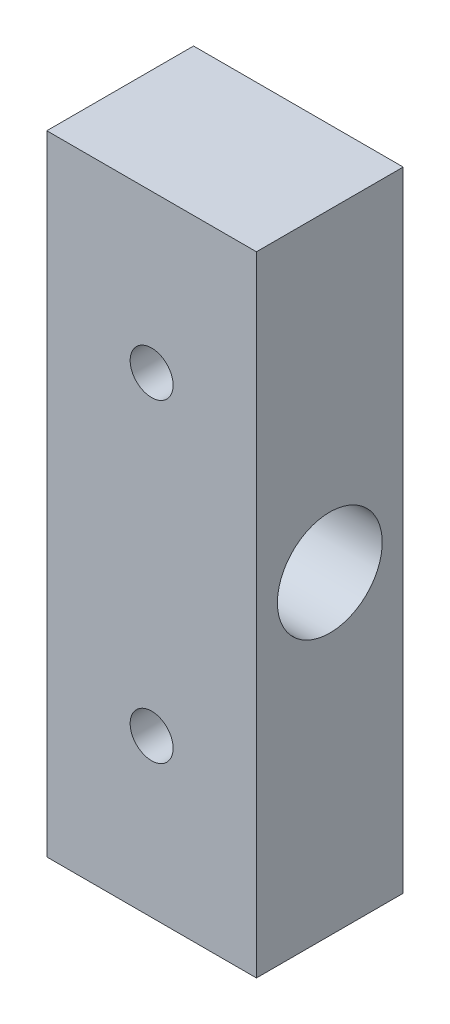
SolidWorks part; units mm, degrees
ref_plane "前视基准面" through (0, 0, 0) normal (0, 0, 1) x (1, 0, 0)
ref_plane "上视基准面" through (0, 0, 0) normal (0, 1, 0) x (1, 0, 0)
ref_plane "右视基准面" through (0, 0, 0) normal (1, 0, 0) x (0, 0, -1)
other "Configuration Table"
sketch "草图1" plane through (0, 0, 0) normal (0, 1, 0) x (1, 0, 0)
  line L1 (-10, 7) -> (10, 7)
  line L2 (-10, 7) -> (-10, -7)
  line L3 (-10, -7) -> (10, -7)
  line L4 (10, 7) -> (10, -7)
  line L5 (-10, 7) -> (10, -7) construction
  line L6 (-10, -7) -> (10, 7) construction
  point P0 (0, 0)
  dimension "D1" = 14
  dimension "D2" = 20
extrude "凸台-拉伸1" add sketch "草图1" along normal blind 60
sketch "草图2" plane through (-10, 0, 0) normal (-1, 0, 0) x (0, 0, 1)
  line L0 (7, 60) -> (-7, 0) construction
  line L1 (-7, 60) -> (7, 0) construction
  circle A0 centre (0, 30) radius 5
  point P10 (0, 30)
  point P11 (0, 30)
  point P12 (0, 30)
  dimension "D1" = 10
extrude "切除-拉伸1" cut sketch "草图2" against normal up to next
sketch "草图3" plane through (0, 0, -7) normal (0, 0, -1) x (-1, 0, 0)
  line L0 (0, 60) -> (0, 0) construction
  line L1 (-10, 60) -> (10, 60) construction
  line L2 (10, 30) -> (-10, 30) construction
  line L3 (10, 60) -> (10, 0) construction
  line L4 (-10, 60) -> (-10, 0) construction
  circle A0 centre (0, 45) radius 2.05
  circle A1 centre (0, 15) radius 2.05
  dimension "D1" = 4.1
  dimension "D2" = 15
extrude "切除-拉伸2" cut sketch "草图3" against normal up to next
